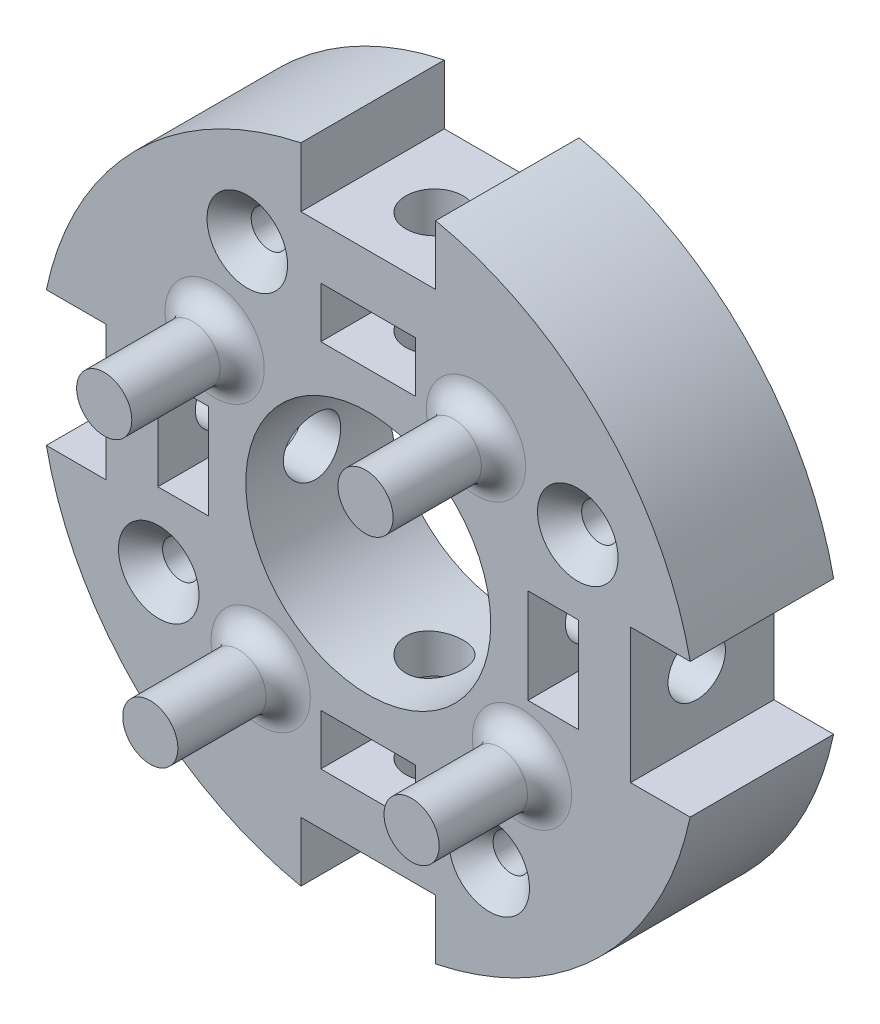
SolidWorks part; units mm, degrees
ref_plane "Plan de face" through (0, 0, 0) normal (0, 0, 1) x (1, 0, 0)
ref_plane "Plan de dessus" through (0, 0, 0) normal (0, 1, 0) x (1, 0, 0)
ref_plane "Plan de droite" through (0, 0, 0) normal (1, 0, 0) x (0, 0, -1)
sketch "Esquisse1" plane through (0, 0, 0) normal (0, 0, 1) x (1, 0, 0)
  line L1 (-29.4129, -5.9059) -> (-23.9629, -5.9059) construction
  line L3 (-29.4129, 5.9059) -> (-23.9629, 5.9059) construction
  line L4 (-23.9629, -5.9059) -> (-23.9629, 5.9059) construction
  line L5 (-29.4129, -5.9059) -> (-23.9629, 5.9059) construction
  line L6 (-29.4129, 5.9059) -> (-23.9629, -5.9059) construction
  line L7 (-5.9059, 29.4129) -> (-5.9059, 23.9629) construction
  line L8 (-5.9059, 23.9629) -> (5.9059, 23.9629) construction
  line L9 (5.9059, 29.4129) -> (5.9059, 23.9629) construction
  line L11 (29.4129, 5.9059) -> (23.9629, 5.9059) construction
  line L12 (23.9629, 5.9059) -> (23.9629, -5.9059) construction
  line L13 (29.4129, -5.9059) -> (23.9629, -5.9059) construction
  line L15 (5.9059, -29.4129) -> (5.9059, -23.9629) construction
  line L16 (5.9059, -23.9629) -> (-5.9059, -23.9629) construction
  line L17 (-5.9059, -29.4129) -> (-5.9059, -23.9629) construction
  line L18 (-6.1059, 29.1677) -> (-6.1059, 23.7629)
  line L19 (-6.1059, 23.7629) -> (6.1059, 23.7629)
  line L20 (6.1059, 29.1677) -> (6.1059, 23.7629)
  line L21 (29.1677, 6.1059) -> (23.7629, 6.1059)
  line L22 (23.7629, 6.1059) -> (23.7629, -6.1059)
  line L23 (29.1677, -6.1059) -> (23.7629, -6.1059)
  line L24 (6.1059, -29.1677) -> (6.1059, -23.7629)
  line L25 (6.1059, -23.7629) -> (-6.1059, -23.7629)
  line L26 (-6.1059, -29.1677) -> (-6.1059, -23.7629)
  line L27 (-29.1677, -6.1059) -> (-23.7629, -6.1059)
  line L28 (-23.7629, -6.1059) -> (-23.7629, 6.1059)
  line L29 (-29.1677, 6.1059) -> (-23.7629, 6.1059)
  line L30 (-4.3, 19.0629) -> (4.3, 19.0629)
  line L31 (-4, 18.7629) -> (4, 18.7629) construction
  line L32 (-4, 18.7629) -> (-4, 14.7629) construction
  line L33 (-4, 14.7629) -> (4, 14.7629) construction
  line L34 (4, 18.7629) -> (4, 14.7629) construction
  line L35 (-4, 18.7629) -> (4, 14.7629) construction
  line L36 (-4, 14.7629) -> (4, 18.7629) construction
  line L37 (4.3, 19.0629) -> (4.3, 14.4629)
  line L38 (-4.3, 14.4629) -> (4.3, 14.4629)
  line L39 (-4.3, 19.0629) -> (-4.3, 14.4629)
  line L40 (19.0629, 4.3) -> (19.0629, -4.3)
  line L41 (19.0629, -4.3) -> (14.4629, -4.3)
  line L42 (14.4629, 4.3) -> (14.4629, -4.3)
  line L43 (19.0629, 4.3) -> (14.4629, 4.3)
  line L44 (4.3, -19.0629) -> (-4.3, -19.0629)
  line L45 (-4.3, -19.0629) -> (-4.3, -14.4629)
  line L46 (4.3, -14.4629) -> (-4.3, -14.4629)
  line L47 (4.3, -19.0629) -> (4.3, -14.4629)
  line L48 (-19.0629, -4.3) -> (-19.0629, 4.3)
  line L49 (-19.0629, 4.3) -> (-14.4629, 4.3)
  line L50 (-14.4629, -4.3) -> (-14.4629, 4.3)
  line L51 (-19.0629, -4.3) -> (-14.4629, -4.3)
  line L52 (-0.2119, 0.3671) -> (-25000.2119, 43301.6373) construction
  line L54 (0, -1000) -> (0, 49000) construction
  arc A0 (-29.4129, -5.9059) -> (-5.9059, -29.4129) centre (0, 0) ccw construction
  circle A1 centre (0, 0) radius 11.1
  circle A2 centre (-10.9602, 18.9835) radius 1.65
  circle A3 centre (18.9835, 10.9602) radius 1.65
  circle A4 centre (10.9602, -18.9835) radius 1.65
  circle A5 centre (-18.9835, -10.9602) radius 1.65
  arc A6 (5.9059, -29.4129) -> (29.4129, -5.9059) centre (0, 0) ccw construction
  arc A7 (29.4129, 5.9059) -> (5.9059, 29.4129) centre (0, 0) ccw construction
  arc A8 (-5.9059, 29.4129) -> (-29.4129, 5.9059) centre (0, 0) ccw construction
  arc A9 (29.1677, 6.1059) -> (6.1059, 29.1677) centre (0, 0) ccw
  arc A10 (6.1059, -29.1677) -> (29.1677, -6.1059) centre (0, 0) ccw
  arc A11 (-29.1677, -6.1059) -> (-6.1059, -29.1677) centre (0, 0) ccw
  arc A12 (-6.1059, 29.1677) -> (-29.1677, 6.1059) centre (0, 0) ccw
  point P4 (-26.6879, 0)
  point P22 (0, 0)
  point P33 (0, 0)
  point P51 (0, 16.7629)
  point P56 (0, 23.7629)
  point P62 (-10.9602, 19.0629)
  point P75 (0, 0)
  point P90 (0, 0)
  dimension "D1" = 60
  dimension "D2" = 22.2
  dimension "D7" = 3.3
  dimension "D3" = 5.45
  dimension "D4" = 4
  dimension "D5" = 21.9203
  dimension "D6" = 0.2
  dimension "D9" = 8
  dimension "D10" = 4
  dimension "D11" = 5
  dimension "D16" = 30
  dimension "D12" = 0.3
  dimension "D8" = 4
  dimension "D13" = 4
extrude "Boss.-Extru.1" add sketch "Esquisse1" along normal blind 13
chamfer "Chanfrein1" distance 2 angle 45 4 edges at (-17.3335, -10.9602, 13) (12.6102, -18.9835, 13) (20.6335, 10.9602, 13) (-9.3102, 18.9835, 13)
sketch "Esquisse6" plane through (-23.7629, 0, 0) normal (-1, 0, 0) x (0, 0, 1)
  line L1 (13, -6.1059) -> (13, 6.1059) construction
  circle A0 centre (7, 0) radius 2.6
  dimension "D1" = 5.2
  dimension "D2" = 6
extrude "Enlèv. mat.-Extru.4" cut sketch "Esquisse6" against normal blind 17
pattern_circular "Répétition circulaire1" count 4 over 360 of "Enlèv. mat.-Extru.4"
sketch "Esquisse7" plane through (0, 0, 13) normal (0, 0, 1) x (1, 0, 0)
  line L0 (-1000, 0) -> (49000, 0) construction
  line L1 (0, 0) -> (-40957.6022, 28678.8218) construction
  circle A0 centre (-13.9256, 9.7508) radius 2.5
  circle A1 centre (9.7508, 13.9256) radius 2.5
  circle A2 centre (13.9256, -9.7508) radius 2.5
  circle A3 centre (-9.7508, -13.9256) radius 2.5
  point P16 (0, 0)
  dimension "D3" = 5
  dimension "D1" = 35
  dimension "D2" = 17
extrude "Boss.-Extru.2" add sketch "Esquisse7" along normal blind 10
fillet "Congé1" radius 2 4 edges at (16.4256, -9.7508, 13) (12.2508, 13.9256, 13) (-11.4256, 9.7508, 13) (-7.2508, -13.9256, 13)
